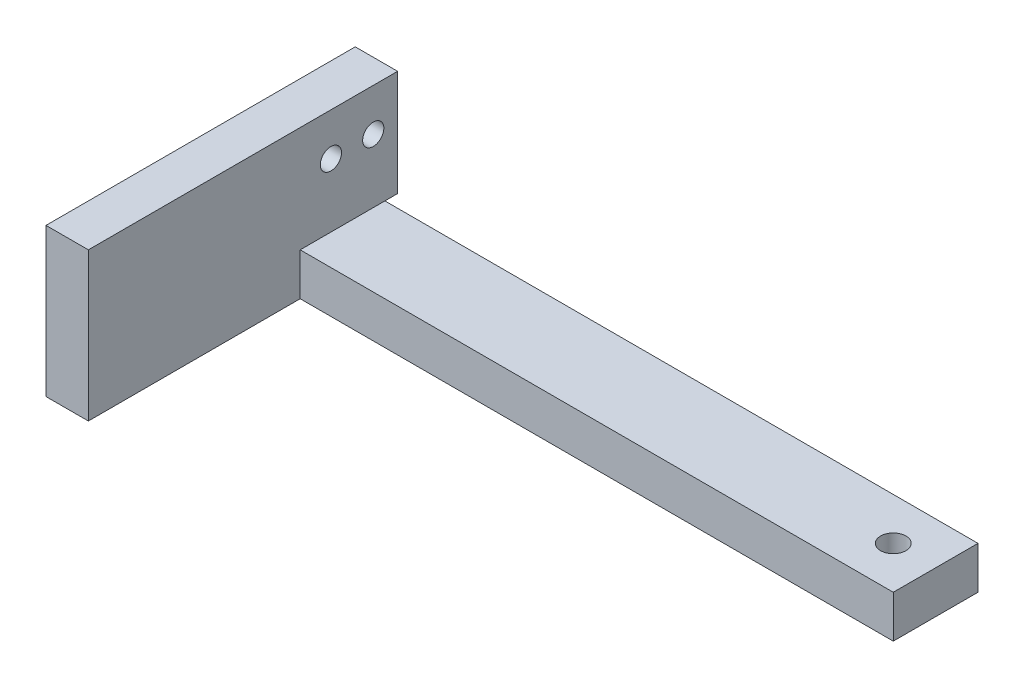
SolidWorks part; units mm, degrees
material "1060 Alloy"
ref_plane "Front Plane" through (0, 0, 0) normal (0, 0, 1) x (1, 0, 0)
ref_plane "Top Plane" through (0, 0, 0) normal (0, 1, 0) x (1, 0, 0)
ref_plane "Right Plane" through (0, 0, 0) normal (1, 0, 0) x (0, 0, -1)
sketch "Sketch1" plane through (0, 0, 0) normal (0, 1, 0) x (1, 0, 0)
  line L1 (-2547.7707, 451.1677) -> (-2397.7707, 451.1677)
  line L2 (-2547.7707, 451.1677) -> (-2547.7707, 431.1677)
  line L3 (-2547.7707, 431.1677) -> (-2397.7707, 431.1677)
  line L4 (-2397.7707, 451.1677) -> (-2397.7707, 431.1677)
  dimension "D1" = 150
  dimension "D2" = 20
extrude "Boss-Extrude1" add sketch "Sketch1" along normal blind 10
sketch "Sketch2" plane through (0, 10, 0) normal (0, 1, 0) x (1, 0, 0)
  line L0 (-2397.7707, 431.1677) -> (-2397.7707, 451.1677) construction
  circle A0 centre (-2407.7707, 441.1677) radius 3
  point P4 (-2397.7707, 441.1677)
  dimension "D1" = 6
  dimension "D2" = 10
extrude "Cut-Extrude1" cut sketch "Sketch2" against normal blind 10
sketch "Sketch3" plane through (-2547.7707, 0, 0) normal (-1, 0, 0) x (0, 0, 1)
  line L1 (-451.1677, 10) -> (-431.1677, 10) construction
  line L2 (-454.1677, 35) -> (-431.1677, 35)
  line L3 (-454.1677, 35) -> (-454.1677, 10)
  line L4 (-454.1677, 10) -> (-431.1677, 10)
  line L5 (-431.1677, 35) -> (-431.1677, 10)
  line L6 (-454.1677, 35) -> (-431.1677, 10) construction
  line L7 (-454.1677, 10) -> (-431.1677, 35) construction
  line L8 (-431.1677, 10) -> (-431.1677, 0) construction
  point P2 (-442.6677, 22.5)
  dimension "D1" = 23
  dimension "D2" = 25
extrude "Boss-Extrude2" add sketch "Sketch3" against normal blind 10
sketch "Sketch4" plane through (-2547.7707, 0, 0) normal (-1, 0, 0) x (0, 0, 1)
  line L0 (-431.1677, 35) -> (-454.1677, 35) construction
  line L1 (-454.1677, 35) -> (-454.1677, 10) construction
  circle A0 centre (-448.4177, 25) radius 2.5
  circle A2 centre (-438.4177, 25) radius 2.5
  dimension "D1" = 5
  dimension "D2" = 5
  dimension "D3" = 10
  dimension "D4" = 10
  dimension "D5" = 5.75
extrude "Cut-Extrude2" cut sketch "Sketch4" against normal through all
sketch "Sketch5" plane through (0, 0, -431.1677) normal (0, 0, 1) x (1, 0, 0)
  line L0 (-2537.7707, 10) -> (-2537.7707, 35) construction
  line L1 (-2547.7707, 35) -> (-2537.7707, 35)
  line L2 (-2547.7707, 35) -> (-2547.7707, 0)
  line L3 (-2547.7707, 0) -> (-2537.7707, 0)
  line L4 (-2537.7707, 35) -> (-2537.7707, 0)
  line L5 (-2547.7707, 35) -> (-2537.7707, 0) construction
  line L6 (-2547.7707, 0) -> (-2537.7707, 35) construction
  line L7 (-2547.7707, 35) -> (-2547.7707, 0) construction
  line L8 (-2537.7707, 35) -> (-2547.7707, 35) construction
  line L9 (-2547.7707, 0) -> (-2397.7707, 0) construction
  point P0 (-2542.7707, 17.5)
extrude "Boss-Extrude3" add sketch "Sketch5" along normal blind 50
